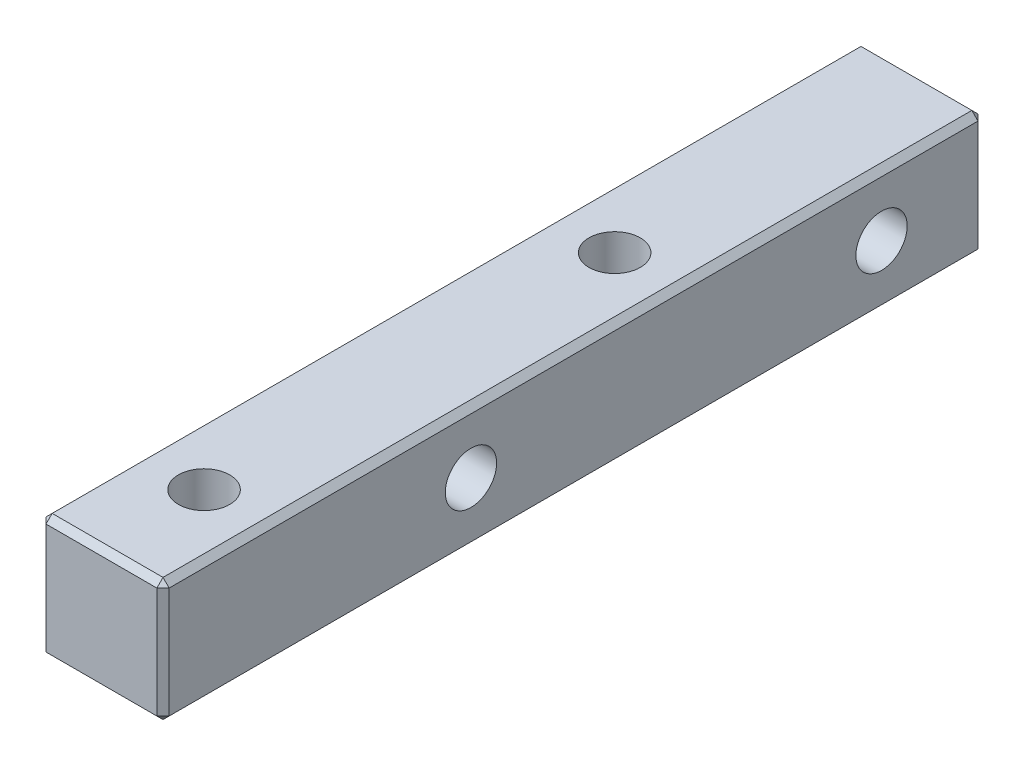
SolidWorks part; units mm, degrees
material "6061 合金"
ref_plane "前视基准面" through (0, 0, 0) normal (0, 0, 1) x (1, 0, 0)
ref_plane "上视基准面" through (0, 0, 0) normal (0, 1, 0) x (1, 0, 0)
ref_plane "右视基准面" through (0, 0, 0) normal (1, 0, 0) x (0, 0, -1)
sketch "草图1" plane through (0, 0, 0) normal (0, 0, 1) x (1, 0, 0)
  line L1 (-3, -3) -> (3, -3)
  line L2 (-3, -3) -> (-3, 3)
  line L3 (-3, 3) -> (3, 3)
  line L4 (3, -3) -> (3, 3)
  line L5 (0, 3) -> (0, -3) construction
  line L6 (-3, 0) -> (3, 0) construction
  point P0 (0, 0)
  dimension "D1" = 6
extrude "凸台-拉伸1" add sketch "草图1" along normal mid plane 40
sketch "草图2" plane through (-3, 0, 0) normal (-1, 0, 0) x (0, 0, 1)
  line L0 (-15, 0) -> (5, 0) construction
  line L1 (-20, 3) -> (-20, -3) construction
  dimension "D1" = 5
  dimension "D2" = 20
sketch "草图3" plane through (0, 3, 0) normal (0, 1, 0) x (1, 0, 0)
  line L0 (0, -15) -> (0, 5) construction
  line L1 (3, -20) -> (-3, -20) construction
  dimension "D1" = 5
  dimension "D2" = 20
hole_wizard " 螺纹孔1" positions "草图4" profile "草图5" tap size "M3" standard "GB" end condition up to next
sketch "草图4" plane through (-3, 0, 0) normal (-1, 0, 0) x (0, 0, 1)
  point P0 (-15, 0)
  point P3 (5, 0)
sketch "草图5" plane through (-3, 0, -15) normal (0, 1, 0) x (0, 0, 1)
  line L0 (0, 0) -> (0, 6)
  line L1 (0, 6) -> (1.25, 6)
  line L2 (1.25, 6) -> (1.25, 0)
  line L5 (1.25, 0) -> (0, 0)
  line L11 (0, -6.35) -> (0, 107.95) construction
  dimension "通孔螺纹孔钻头直径" = 2.5
  dimension "通孔螺纹孔钻头深度" = 6
cosmetic thread "孔螺蚊线1" parameters "D2"=3
cosmetic thread "孔螺蚊线2" parameters "D2"=3
hole_wizard " 螺纹孔2" positions "草图6" profile "草图7" tap size "M3" standard "GB" end condition up to next
sketch "草图6" plane through (0, 3, 0) normal (0, 1, 0) x (1, 0, 0)
  point P0 (0, 5)
  point P3 (0, -15)
sketch "草图7" plane through (0, 3, -5) normal (1, 0, 0) x (0, 0, 1)
  line L0 (0, 0) -> (0, 6)
  line L1 (0, 6) -> (1.25, 6)
  line L2 (1.25, 6) -> (1.25, 0)
  line L5 (1.25, 0) -> (0, 0)
  line L11 (0, -6.35) -> (0, 107.95) construction
  dimension "通孔螺纹孔钻头直径" = 2.5
  dimension "通孔螺纹孔钻头深度" = 6
cosmetic thread "孔螺蚊线3" parameters "D2"=3
cosmetic thread "孔螺蚊线4" parameters "D2"=3
chamfer "倒角1" distance 0.3 angle 45 12 edges at (-3, -3, 0) (3, 0, 20) (3, -3, 0) (0, -3, 20) (0, -3, -20) (-3, 0, -20) (3, 0, -20) (3, 3, 0) (0, 3, 20) (-3, 0, 20) (-3, 3, 0) (0, 3, -20)
